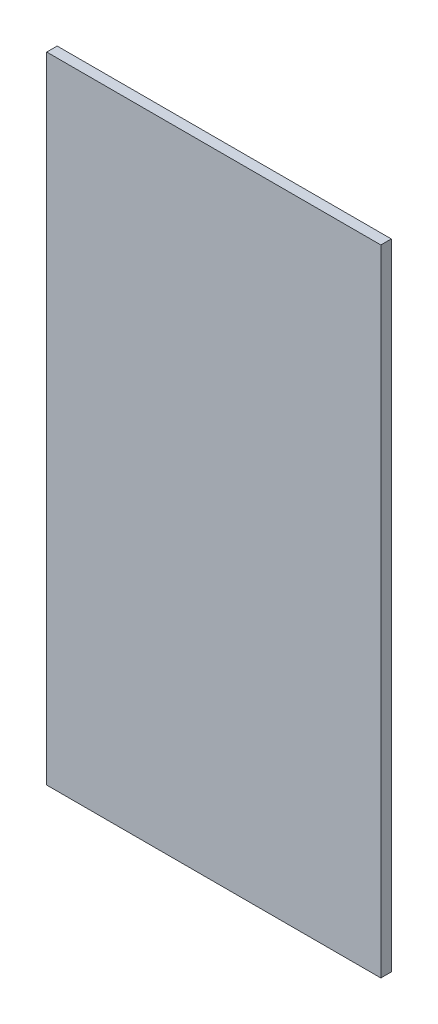
SolidWorks part; units mm, degrees
ref_plane "Front Plane" through (0, 0, 0) normal (0, 0, 1) x (1, 0, 0)
ref_plane "Top Plane" through (0, 0, 0) normal (0, 1, 0) x (1, 0, 0)
ref_plane "Right Plane" through (0, 0, 0) normal (1, 0, 0) x (0, 0, -1)
sketch "Sketch3" plane through (0, 0, 0) normal (0, 0, 1) x (1, 0, 0)
  line L1 (0, 0) -> (50.8, 0)
  line L2 (0, 0) -> (0, 96.52)
  line L3 (0, 96.52) -> (50.8, 96.52)
  line L4 (50.8, 0) -> (50.8, 96.52)
  dimension "D1" = 96.52
  dimension "D2" = 50.8
extrude "Boss-Extrude1" add sketch "Sketch3" along normal blind 1.5875
